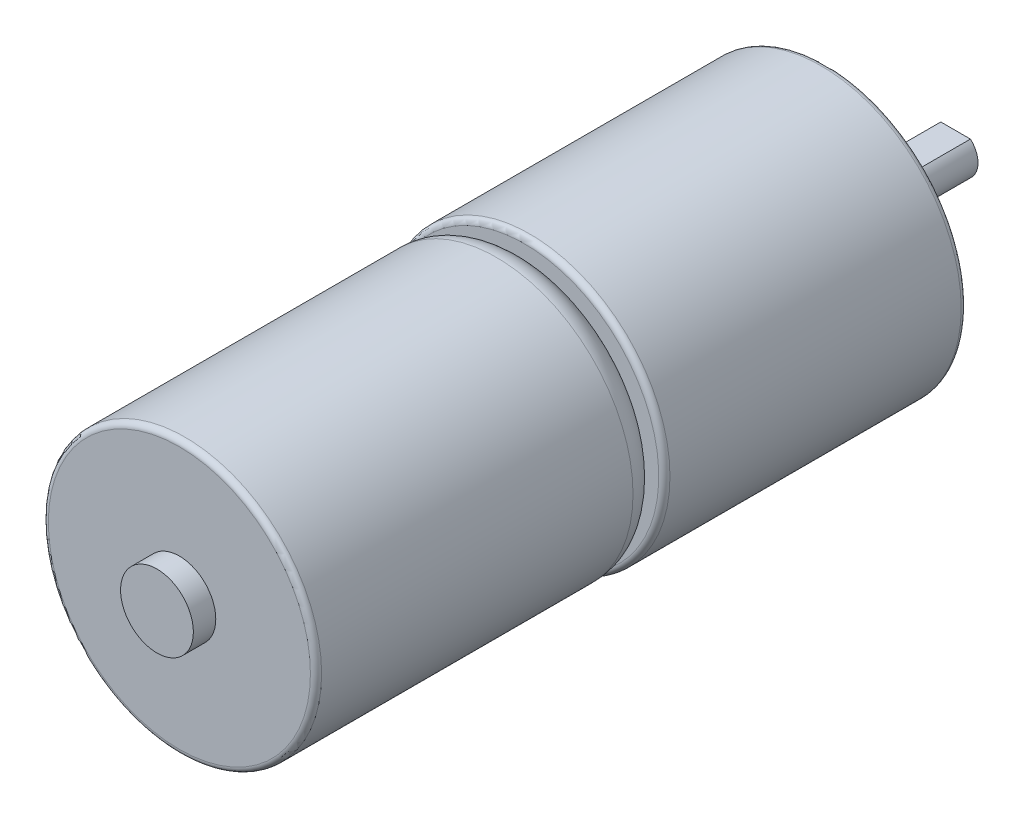
SolidWorks part; units mm, degrees
ref_plane "正面" through (0, 0, 0) normal (0, 0, 1) x (1, 0, 0)
ref_plane "平面" through (0, 0, 0) normal (0, 1, 0) x (1, 0, 0)
ref_plane "右側面" through (0, 0, 0) normal (1, 0, 0) x (0, 0, -1)
sketch "ｽｹｯﾁ1" plane through (0, 0, 0) normal (0, 0, 1) x (1, 0, 0)
  circle A0 centre (0, 0) radius 12.2
  dimension "D1" = 24.4
extrude "ﾎﾞｽ - 押し出し1" add sketch "ｽｹｯﾁ1" along normal blind 30.8
sketch "ｽｹｯﾁ2" plane through (0, 0, 30.8) normal (0, 0, 1) x (1, 0, 0)
  circle A0 centre (0, 0) radius 3.25
  dimension "D1" = 6.5
extrude "ﾎﾞｽ - 押し出し2" add sketch "ｽｹｯﾁ2" along normal blind 2
fillet "ﾌｨﾚｯﾄ1" radius 2.5 1 edges at (12.2, 0, 0)
sketch "ｽｹｯﾁ3" plane through (0, 0, 0) normal (0, 0, -1) x (-1, 0, 0)
  circle A0 centre (0, 0) radius 12.5
  dimension "D1" = 25
extrude "ﾎﾞｽ - 押し出し3" add sketch "ｽｹｯﾁ3" along normal blind 27
sketch "ｽｹｯﾁ4" plane through (0, 0, -27) normal (0, 0, -1) x (-1, 0, 0)
  circle A0 centre (0, 0) radius 3.5
  dimension "D1" = 7
extrude "ﾎﾞｽ - 押し出し4" add sketch "ｽｹｯﾁ4" along normal blind 2.5
sketch "ｽｹｯﾁ5" plane through (0, 0, -29.5) normal (0, 0, -1) x (-1, 0, 0)
  circle A0 centre (0, 0) radius 2
  dimension "D1" = 4
extrude "ﾎﾞｽ - 押し出し5" add sketch "ｽｹｯﾁ5" along normal blind 9
sketch "ｽｹｯﾁ6" plane through (0, 0, -38.5) normal (0, 0, -1) x (-1, 0, 0)
  line L0 (-1.3229, 1.5) -> (1.3229, 1.5)
  line L1 (0, -2) -> (1.8426, -2) construction
  circle A0 centre (0, 0) radius 2 construction
  arc A1 (1.3229, 1.5) -> (-1.3229, 1.5) centre (0, 0) ccw
  point P2 (0, 0)
  dimension "D1" = 3.5
extrude "ｶｯﾄ - 押し出し1" cut sketch "ｽｹｯﾁ6" against normal blind 8
sketch "ｽｹｯﾁ7" plane through (0, 0, -27) normal (0, 0, -1) x (-1, 0, 0)
  circle A0 centre (0, 0) radius 8.5 construction
  circle A1 centre (0, 8.5) radius 1.5
  circle A2 centre (8.5, 0) radius 1.5
  circle A3 centre (0, -8.5) radius 1.5
  circle A4 centre (-8.5, 0) radius 1.5
  point P5 (-7.6606, -0.2554)
  point P6 (-1.2177, -7.0758)
  point P14 (0, 0)
  dimension "D1" = 17
  dimension "D2" = 3
  dimension "D3" = 4
extrude "ｶｯﾄ - 押し出し2" cut sketch "ｽｹｯﾁ7" against normal blind 18
fillet "ﾌｨﾚｯﾄ2" radius 0.5 3 edges at (-12.5, 0, -27) (-12.5, 0, 0) (12.2, 0, 30.8)
sketch "ｽｹｯﾁ8" plane through (0, 0, -27) normal (0, 0, -1) x (-1, 0, 0)
  circle A0 centre (0, 8.5) radius 3.25
  circle A1 centre (0, -8.5) radius 3.25
  dimension "6.5" = 6.5
extrude "ｶｯﾄ - 押し出し3" cut sketch "ｽｹｯﾁ8" against normal blind 5
